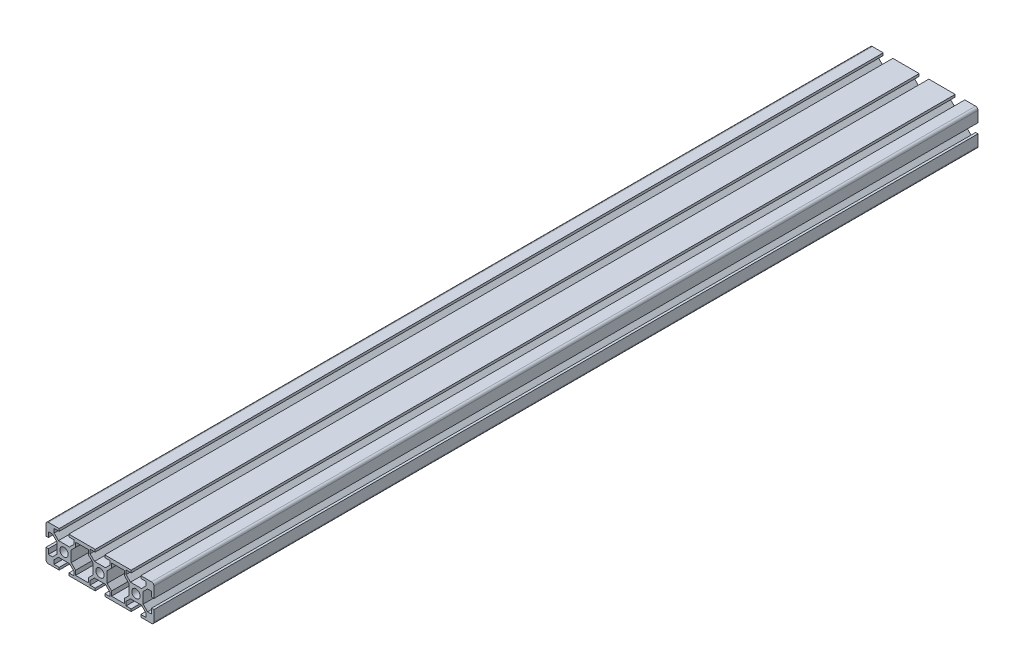
SolidWorks part; units mm, degrees
ref_plane "Front Plane" through (0, 0, 0) normal (0, 0, 1) x (1, 0, 0)
ref_plane "Top Plane" through (0, 0, 0) normal (0, 1, 0) x (1, 0, 0)
ref_plane "Right Plane" through (0, 0, 0) normal (1, 0, 0) x (0, 0, -1)
sketch "Sketch1" plane through (0, 0, 0) normal (0, 0, 1) x (1, 0, 0)
  line L1 (-45, 0) -> (45, 0)
  line L2 (-45, 0) -> (-45, 30)
  line L3 (-45, 30) -> (45, 30)
  line L4 (45, 0) -> (45, 30)
  point P4 (0, 0)
  dimension "D1" = 90
  dimension "D2" = 30
extrude "Boss-Extrude1" add sketch "Sketch1" along normal mid plane 687
hole_wizard "M8x1.0 Tapped Hole1" positions "Sketch2" profile "Sketch3" tap size "M8x1.0" standard "ANSI Metric"
sketch "Sketch2" plane through (0, 0, 343.5) normal (0, 0, 1) x (1, 0, 0)
  line L0 (45, 0) -> (30, 15) construction
  line L2 (45, 0) -> (45, 30) construction
  line L3 (45, 0) -> (45, 30) construction
  line L4 (0, 0) -> (0, 30) construction
  line L5 (-45, 0) -> (45, 0) construction
  line L6 (45, 30) -> (-45, 30) construction
  point P0 (30, 15)
  point P2 (-30, 15)
  point P12 (45, 15)
  point P21 (0, 15)
  dimension "D1" = 45
sketch "Sketch3" plane through (30, 15, 343.5) normal (1, 0, 0) x (0, -1, 0)
  line L0 (0, 0) -> (0, 21.103)
  line L1 (0, 21.103) -> (3.5, 19)
  line L2 (3.5, 19) -> (3.5, 0)
  line L5 (3.5, 0) -> (0, 0)
  line L10 (0, 21.103) -> (-3.5, 19) construction
  line L11 (0, -6.35) -> (0, 107.95) construction
  dimension "Tap Drill Dia." = 7
  dimension "Tap Drill Depth" = 19
  dimension "Drill Angle" = 118
cosmetic thread "Hole Thread1" parameters "D1"=16, "D2"=8
cosmetic thread "Hole Thread2" parameters "D1"=16, "D2"=8
cosmetic thread "Hole Thread5" parameters "D1"=16, "D2"=8
mirror "Mirror1" about plane through (0, 0, 0) normal (0, 0, 1) of "M8x1.0 Tapped Hole1"
cosmetic thread "Hole Thread3" parameters "D1"=16, "D2"=8
cosmetic thread "Hole Thread4" parameters "D1"=16, "D2"=8
cosmetic thread "Hole Thread6" parameters "D1"=16, "D2"=8
sketch "Sketch4" plane through (0, 0, 343.5) normal (0, 0, 1) x (1, 0, 0)
  line L0 (-45, 19) -> (-43, 19)
  line L1 (-34.5858, 9) -> (-25.4142, 9)
  line L2 (-36, 10.4142) -> (-36, 19.5858)
  line L3 (-34.5858, 21) -> (-25.4142, 21)
  line L4 (-24, 10.4142) -> (-24, 19.5858)
  line L5 (-36, 9) -> (-24, 21) construction
  line L6 (-36, 21) -> (-24, 9) construction
  line L11 (6, 21) -> (-6, 9) construction
  line L12 (6, 9) -> (-6, 21) construction
  line L13 (-45, 30) -> (-45, 0) construction
  line L14 (-43, 19) -> (-43, 23.25)
  line L15 (-43, 23.25) -> (-39.6642, 23.25)
  line L16 (-39.6642, 23.25) -> (-36, 19.5858)
  line L17 (-36, 19.5858) -> (-36, 10.4142)
  line L18 (-45, 15) -> (-36, 15) construction
  line L19 (-45, 19) -> (-45, 15)
  line L20 (-45, 15) -> (-45, 11)
  line L21 (-45, 11) -> (-43, 11)
  line L22 (-43, 11) -> (-43, 6.75)
  line L23 (-43, 6.75) -> (-39.6642, 6.75)
  line L24 (-39.6642, 6.75) -> (-36, 10.4142)
  line L25 (-38.25, 24.6642) -> (-34.5858, 21)
  line L26 (-38.25, 28) -> (-38.25, 24.6642)
  line L27 (-34, 28) -> (-38.25, 28)
  line L28 (-34, 30) -> (-34, 28)
  line L29 (-30, 30) -> (-34, 30)
  line L30 (-26, 30) -> (-30, 30)
  line L31 (-26, 30) -> (-26, 28)
  line L32 (-26, 28) -> (-21.75, 28)
  line L33 (-21.75, 28) -> (-21.75, 24.6642)
  line L34 (-21.75, 24.6642) -> (-25.4142, 21)
  line L35 (-20.3358, 23.25) -> (-24, 19.5858)
  line L36 (-17, 23.25) -> (-20.3358, 23.25) construction
  line L37 (-17, 6.75) -> (-13, 6.75) construction
  line L38 (-15, 6.75) -> (-15, 11) construction
  line L39 (-15, 15) -> (-15, 19) construction
  line L40 (-15, 11) -> (-15, 15) construction
  line L41 (-15, 19) -> (-15, 23.25) construction
  line L42 (-13, 23.25) -> (-17, 23.25) construction
  line L43 (-17, 6.75) -> (-20.3358, 6.75) construction
  line L44 (-20.3358, 6.75) -> (-24, 10.4142)
  line L45 (-21.75, 5.3358) -> (-25.4142, 9)
  line L46 (-21.75, 2) -> (-21.75, 5.3358)
  line L47 (-26, 2) -> (-21.75, 2)
  line L48 (-26, 0) -> (-26, 2)
  line L49 (-30, 0) -> (-26, 0)
  line L50 (-34, 0) -> (-30, 0)
  line L51 (-34, 0) -> (-34, 2)
  line L52 (-34, 2) -> (-38.25, 2)
  line L53 (-38.25, 2) -> (-38.25, 5.3358)
  line L54 (-38.25, 5.3358) -> (-34.5858, 9)
  line L55 (0, 0) -> (-4, 0)
  line L56 (-4, 0) -> (-4, 2)
  line L57 (-15, 19) -> (-17, 19) [skipped]
  line L58 (-17, 19) -> (-17, 23.25) [skipped]
  line L59 (-15, 11) -> (-17, 11) [skipped]
  line L60 (-17, 11) -> (-17, 6.75) [skipped]
  line L61 (-4, 2) -> (-8.25, 2)
  line L62 (-8.25, 2) -> (-8.25, 5.3358)
  line L63 (-8.25, 5.3358) -> (-4.5858, 9)
  line L64 (-9.6642, 6.75) -> (-6, 10.4142)
  line L65 (-13, 6.75) -> (-9.6642, 6.75) construction
  line L66 (-13, 23.25) -> (-9.6642, 23.25) construction
  line L67 (-9.6642, 23.25) -> (-6, 19.5858)
  line L68 (-8.25, 24.6642) -> (-4.5858, 21)
  line L69 (-8.25, 28) -> (-8.25, 24.6642)
  line L70 (-4, 28) -> (-8.25, 28)
  line L71 (-4, 30) -> (-4, 28)
  line L72 (-4, 30) -> (0, 30)
  line L73 (-6, 10.4142) -> (-6, 19.5858)
  line L74 (0, 21) -> (-4.5858, 21)
  line L75 (0, 9) -> (-4.5858, 9)
  line L76 (0, 0) -> (0, 30) construction
  line L77 (0, 21) -> (0, 30)
  line L78 (0, 9) -> (0, 0)
  line L79 (-20.3358, 23.25) -> (-20.3358, 27)
  line L80 (-20.3358, 27) -> (-9.6642, 27)
  line L81 (-9.6642, 27) -> (-9.6642, 23.25)
  line L82 (45, 30) -> (-45, 30) construction
  line L83 (-20.3358, 6.75) -> (-20.3358, 3)
  line L84 (-20.3358, 3) -> (-9.6642, 3)
  line L85 (-9.6642, 3) -> (-9.6642, 6.75)
  line L86 (-45, 0) -> (45, 0) construction
  point P0 (-30, 15)
  point P62 (-30, 15)
  line M63 (-45, 30) -> (-45, 0)
  line M64 (-45, 0) -> (45, 0)
  line M66 (45, 30) -> (-45, 30)
  dimension "D1" = 12
  dimension "D2" = 4
  dimension "D3" = 8.25
  dimension "D4" = 2
  dimension "D5" = 7
  dimension "D6" = 45
  dimension "D7" = 1
  dimension "D9" = 3
  dimension "D10" = 3
  dimension "D8" = 4
extrude "Cut-Extrude1" cut sketch "Sketch4" against normal through all contours L78 L75 L63 L62 L61 L56 M64 | L74 L77 L71 L70 L69 L68 M66 | L54 L53 L52 L51 L48 L47 L46 L45 L1 M64 | L84 L85 L64 L73 L67 L81 L80 L79 L35 L4 L44 L83 | L34 L33 L32 L31 L28 L27 L26 L25 L3 M66 | L23 L24 L2 L16 L15 L14 L0 L21 L22 M63
mirror "Mirror2" about plane through (0, 0, 0) normal (1, 0, 0) of "Cut-Extrude1"
fillet "Fillet1" radius 2 4 edges at (45, 30, 0) (45, 0, 0) (-45, 0, 0) (-45, 30, 0)
